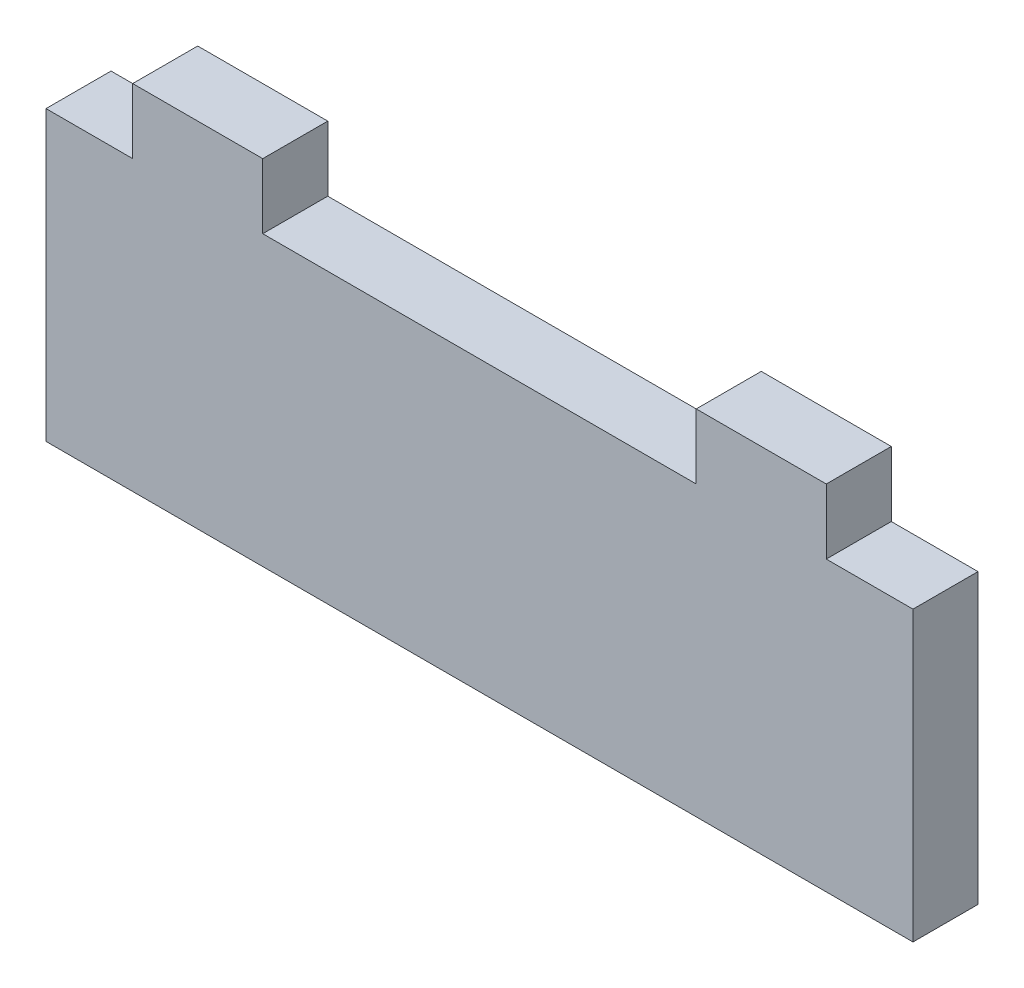
SolidWorks part; units mm, degrees
ref_plane "Front Plane" through (0, 0, 0) normal (0, 0, 1) x (1, 0, 0)
ref_plane "Top Plane" through (0, 0, 0) normal (0, 1, 0) x (1, 0, 0)
ref_plane "Right Plane" through (0, 0, 0) normal (1, 0, 0) x (0, 0, -1)
sketch "Sketch1" plane through (0, 0, 0) normal (0, 0, 1) x (1, 0, 0)
  line L0 (0, 6.65) -> (0, -6.65)
  line L1 (20, -6.65) -> (-20, -6.65)
  line L2 (20, -6.65) -> (20, 6.65)
  line L3 (20, 6.65) -> (-20, 6.65)
  line L4 (-20, -6.65) -> (-20, 6.65)
  line L5 (20, -6.65) -> (-20, 6.65) construction
  line L6 (20, 6.65) -> (-20, -6.65) construction
  line L7 (-16, 6.65) -> (-10, 6.65)
  line L8 (-16, 6.65) -> (-16, 9.65)
  line L9 (-16, 9.65) -> (-10, 9.65)
  line L10 (-10, 6.65) -> (-10, 9.65)
  line L11 (10, 6.65) -> (10, 9.65)
  line L12 (16, 9.65) -> (10, 9.65)
  line L13 (16, 6.65) -> (16, 9.65)
  line L14 (16, 6.65) -> (10, 6.65)
  point P0 (0, 0)
  dimension "D1" = 40
  dimension "D2" = 13.3
  dimension "D3" = 6
  dimension "D4" = 3
  dimension "D5" = 4
  dimension "D6" = 10
extrude "Boss-Extrude1" add sketch "Sketch1" along normal blind 3 contours L4 L1 L0 L3 | L2 L3 L0 L1 | L3 L13 L12 L11 | L3 L10 L9 L8
